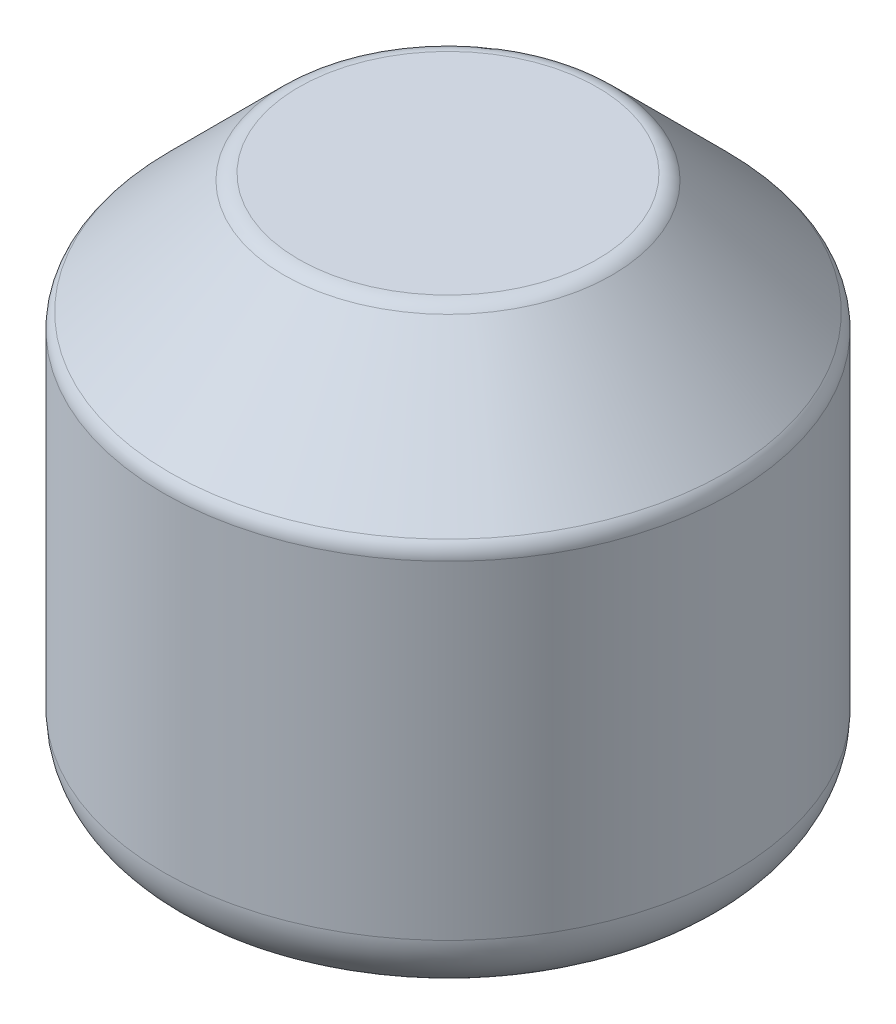
SolidWorks part; units mm, degrees
material "7075-T6 (SN)"
ref_plane "Front Plane" through (0, 0, 0) normal (0, 0, 1) x (1, 0, 0)
ref_plane "Top Plane" through (0, 0, 0) normal (0, 1, 0) x (1, 0, 0)
ref_plane "Right Plane" through (0, 0, 0) normal (1, 0, 0) x (0, 0, -1)
sketch "Sketch1" plane through (0, 0, 0) normal (0, 1, 0) x (1, 0, 0)
  circle A0 centre (0, 0) radius 13.5
  dimension "D1" = 27
extrude "Boss-Extrude1" add sketch "Sketch1" along normal blind 25
chamfer "Chamfer1" distance 6 angle 45 1 edges at (0, 25, 13.5)
fillet "Fillet1" radius 3 1 edges at (0, 0, 13.5)
fillet "Fillet2" radius 1 2 edges at (0, 25, 7.5) (0, 19, 13.5)
